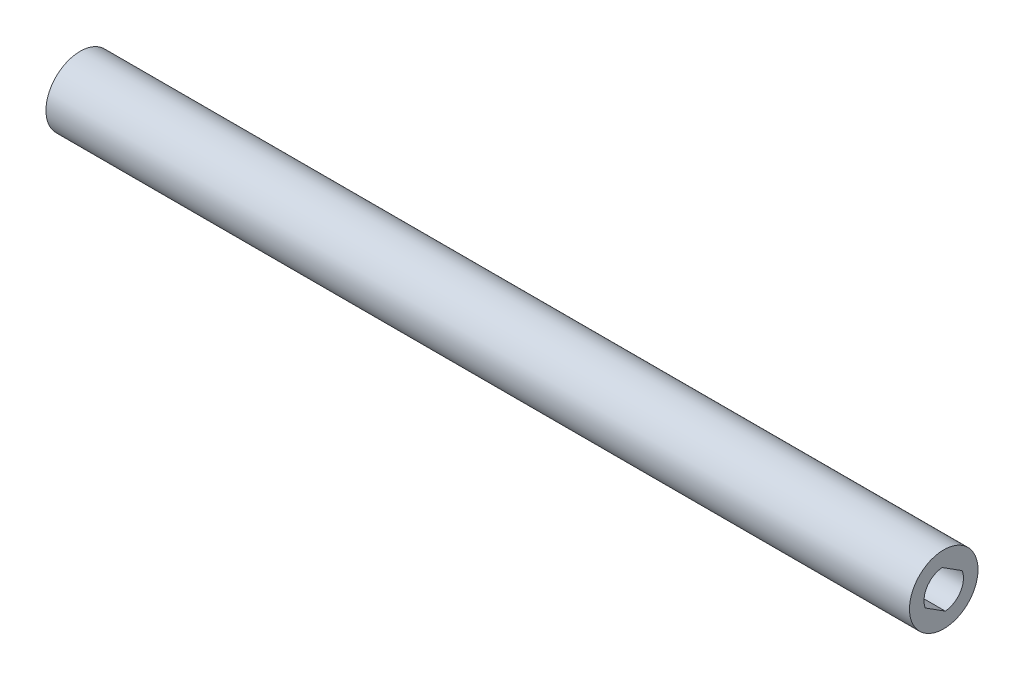
SolidWorks part; units mm, degrees
ref_plane "Front Plane" through (0, 0, 0) normal (0, 0, 1) x (1, 0, 0)
ref_plane "Top Plane" through (0, 0, 0) normal (0, 1, 0) x (1, 0, 0)
ref_plane "Right Plane" through (0, 0, 0) normal (1, 0, 0) x (0, 0, -1)
sketch "Sketch1" plane through (0, 0, 0) normal (1, 0, 0) x (0, 0, -1)
  circle A0 centre (0, 0) radius 5
  dimension "D1" = 10
extrude "Boss-Extrude1" add sketch "Sketch1" along normal blind 126
sketch "Sketch2" plane through (126, 0, 0) normal (1, 0, 0) x (0, 0, -1)
  line L0 (-2.5238, -0.8867) -> (0.2754, -2.6608) construction
  line L1 (-2.5238, -0.8867) -> (0.2754, -2.6608) construction
  line L2 (2.5238, 0.8867) -> (-0.2754, 2.6608) construction
  line L3 (2.5238, 0.8867) -> (-0.2754, 2.6608) construction
  line L4 (-2.6883, -1.0192) -> (0.2257, -2.8661)
  line L5 (2.6883, 1.0192) -> (-0.2257, 2.8661)
  arc A2 (-0.2754, 2.6608) -> (-2.5238, -0.8867) centre (0, 0) ccw construction
  arc A3 (-0.2754, 2.6608) -> (-2.5238, -0.8867) centre (0, 0) ccw construction
  arc A4 (0.2754, -2.6608) -> (2.5238, 0.8867) centre (0, 0) ccw construction
  arc A5 (0.2754, -2.6608) -> (2.5238, 0.8867) centre (0, 0) ccw construction
  arc A6 (0.2257, -2.8661) -> (2.6883, 1.0192) centre (0, 0) ccw
  arc A7 (-0.2257, 2.8661) -> (-2.6883, -1.0192) centre (0, 0) ccw
  dimension "D1" = 0.2
extrude "Cut-Extrude1" cut sketch "Sketch2" against normal blind 8
sketch "Sketch3" plane through (0, 0, 0) normal (-1, 0, 0) x (0, 0, 1)
  line L0 (0.2754, 2.6608) -> (-2.5238, 0.8867) construction
  line L1 (0.2754, 2.6608) -> (-2.5238, 0.8867) construction
  line L2 (-0.2754, -2.6608) -> (2.5238, -0.8867) construction
  line L3 (-0.2754, -2.6608) -> (2.5238, -0.8867) construction
  line L4 (0.2257, 2.8661) -> (-2.6883, 1.0192)
  line L5 (-0.2257, -2.8661) -> (2.6883, -1.0192)
  arc A0 (2.5238, -0.8867) -> (0.2754, 2.6608) centre (0, 0) ccw construction
  arc A1 (2.5238, -0.8867) -> (0.2754, 2.6608) centre (0, 0) ccw construction
  arc A2 (-2.5238, 0.8867) -> (-0.2754, -2.6608) centre (0, 0) ccw construction
  arc A3 (-2.5238, 0.8867) -> (-0.2754, -2.6608) centre (0, 0) ccw construction
  arc A4 (-2.6883, 1.0192) -> (-0.2257, -2.8661) centre (0, 0) ccw
  arc A5 (2.6883, -1.0192) -> (0.2257, 2.8661) centre (0, 0) ccw
  dimension "D1" = 0.2
extrude "Cut-Extrude2" cut sketch "Sketch3" against normal blind 8
